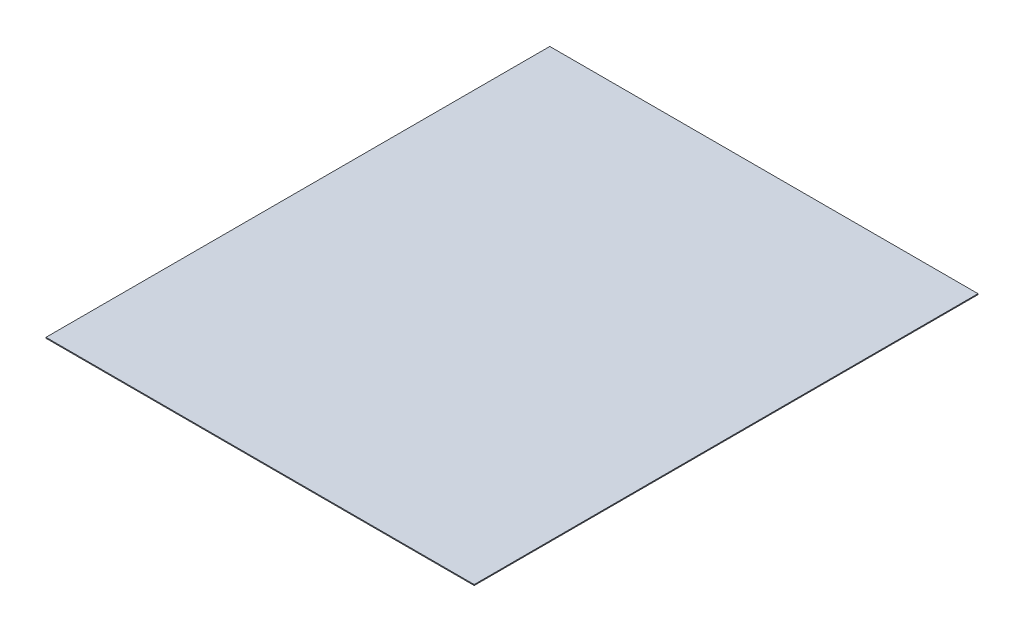
SolidWorks part; units mm, degrees
ref_plane "Front Plane" through (0, 0, 0) normal (0, 0, 1) x (1, 0, 0)
ref_plane "Top Plane" through (0, 0, 0) normal (0, 1, 0) x (1, 0, 0)
ref_plane "Right Plane" through (0, 0, 0) normal (1, 0, 0) x (0, 0, -1)
other "Configuration Table"
sketch "Sketch1" plane through (0, 0, 0) normal (0, 0, 1) x (1, 0, 0)
  line L1 (1.5, 1968.5) -> (698.5, 1968.5)
  line L2 (1.5, 1968.5) -> (1.5, 1970)
  line L3 (1.5, 1970) -> (698.5, 1970)
  line L4 (698.5, 1968.5) -> (698.5, 1970)
extrude "OVEN_dis_ust_1" add sketch "Sketch1" against normal blind 820 separate body
